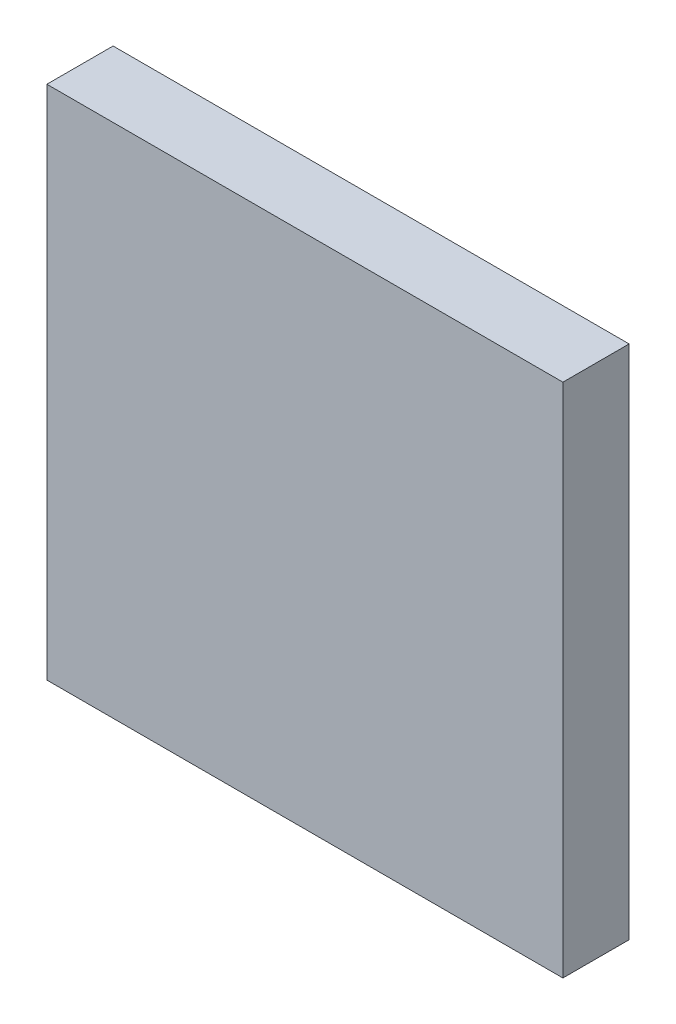
SolidWorks part; units mm, degrees
ref_plane "正面" through (0, 0, 0) normal (0, 0, 1) x (1, 0, 0)
ref_plane "平面" through (0, 0, 0) normal (0, 1, 0) x (1, 0, 0)
ref_plane "右側面" through (0, 0, 0) normal (1, 0, 0) x (0, 0, -1)
sketch "ｽｹｯﾁ1" plane through (0, 0, 0) normal (0, 0, 1) x (1, 0, 0)
  line L0 (-50, 0) -> (50, 0) construction
  line L1 (-50, 50) -> (50, 50)
  line L2 (-50, 50) -> (-50, -50)
  line L3 (-50, -50) -> (50, -50)
  line L4 (50, 50) -> (50, -50)
  line L5 (0, -50) -> (0, 50) construction
  point P8 (0, 0)
  dimension "D1" = 100
  dimension "D2" = 100
  dimension "D3" = 0
  dimension "D4" = 0
extrude "ﾎﾞｽ - 押し出し1" add sketch "ｽｹｯﾁ1" along normal blind 1.6
sketch "ｽｹｯﾁ4" plane through (0, 0, 0) normal (0, 0, -1) x (-1, 0, 0)
  line L0 (-50, -50) -> (-50, 50) construction
  line L1 (11.11, -41.35) -> (28.89, -41.35)
  line L2 (11.11, -41.35) -> (11.11, -43.85)
  line L3 (11.11, -43.85) -> (28.89, -43.85)
  line L4 (28.89, -41.35) -> (28.89, -43.85)
  line L5 (50, -50) -> (-50, -50) construction
  line L6 (50, 50) -> (50, -50) construction
  line L8 (-43.85, -11.11) -> (-41.35, -11.11)
  line L9 (-43.85, -11.11) -> (-43.85, -28.89)
  line L10 (-43.85, -28.89) -> (-41.35, -28.89)
  line L11 (-41.35, -11.11) -> (-41.35, -28.89)
  line L12 (-28.89, 43.85) -> (-11.11, 43.85)
  line L13 (-28.89, 43.85) -> (-28.89, 41.35)
  line L14 (-28.89, 41.35) -> (-11.11, 41.35)
  line L15 (-11.11, 43.85) -> (-11.11, 41.35)
  line L16 (-50, 50) -> (50, 50) construction
  line L18 (41.35, 28.89) -> (43.85, 28.89)
  line L19 (41.35, 28.89) -> (41.35, 11.11)
  line L20 (41.35, 11.11) -> (43.85, 11.11)
  line L21 (43.85, 28.89) -> (43.85, 11.11)
  point P4 (28.89, -42.6)
  point P7 (20, -43.85)
  point P14 (-43.85, -20)
  point P15 (-42.6, -28.89)
  point P22 (-28.89, 42.6)
  point P25 (43.85, 20)
  point P26 (-20, 43.85)
  point P31 (42.6, 28.89)
  dimension "D1" = 7.4
  dimension "D2" = 30
  dimension "D3" = 2.5
  dimension "D4" = 17.78
  dimension "D5" = 2.5
  dimension "D6" = 17.78
  dimension "D7" = 30
  dimension "D8" = 7.4
  dimension "D9" = 2.5
  dimension "D10" = 7.4
  dimension "D11" = 30
  dimension "D12" = 17.78
  dimension "D13" = 17.78
  dimension "D14" = 2.5
  dimension "D15" = 30
  dimension "D16" = 7.4
extrude "ﾎﾞｽ - 押し出し2" add sketch "ｽｹｯﾁ4" along normal blind 2.5
sketch "ｽｹｯﾁ5" plane through (0, 0, -2.5) normal (0, 0, -1) x (-1, 0, 0)
  line L1 (-20.32, 42.92) -> (-19.68, 42.92)
  line L2 (-20.32, 42.92) -> (-20.32, 42.28)
  line L3 (-20.32, 42.28) -> (-19.68, 42.28)
  line L4 (-19.68, 42.92) -> (-19.68, 42.28)
  line L5 (43.85, 28.89) -> (41.35, 28.89) construction
  line L6 (-11.11, 43.85) -> (-28.89, 43.85) construction
  line L7 (-28.89, 43.85) -> (-28.89, 41.35) construction
  line L8 (-43.85, -28.89) -> (-41.35, -28.89) construction
  line L9 (-17.78, 42.92) -> (-17.14, 42.92)
  line L10 (-17.78, 42.92) -> (-17.78, 42.28)
  line L11 (-17.78, 42.28) -> (-17.14, 42.28)
  line L12 (-17.14, 42.92) -> (-17.14, 42.28)
  line L13 (-15.24, 42.92) -> (-14.6, 42.92)
  line L14 (-15.24, 42.92) -> (-15.24, 42.28)
  line L15 (-15.24, 42.28) -> (-14.6, 42.28)
  line L16 (-14.6, 42.92) -> (-14.6, 42.28)
  line L17 (-12.7, 42.92) -> (-12.06, 42.92)
  line L18 (-12.7, 42.92) -> (-12.7, 42.28)
  line L19 (-12.7, 42.28) -> (-12.06, 42.28)
  line L20 (-12.06, 42.92) -> (-12.06, 42.28)
  line L21 (-22.86, 42.92) -> (-22.22, 42.92)
  line L22 (-22.86, 42.92) -> (-22.86, 42.28)
  line L23 (-22.86, 42.28) -> (-22.22, 42.28)
  line L24 (-22.22, 42.92) -> (-22.22, 42.28)
  line L25 (-25.4, 42.92) -> (-24.76, 42.92)
  line L26 (-25.4, 42.92) -> (-25.4, 42.28)
  line L27 (-25.4, 42.28) -> (-24.76, 42.28)
  line L28 (-24.76, 42.92) -> (-24.76, 42.28)
  line L29 (-27.94, 42.92) -> (-27.3, 42.92)
  line L30 (-27.94, 42.92) -> (-27.94, 42.28)
  line L31 (-27.94, 42.28) -> (-27.3, 42.28)
  line L32 (-27.3, 42.92) -> (-27.3, 42.28)
  line L33 (-42.92, -19.68) -> (-42.28, -19.68)
  line L34 (-42.92, -19.68) -> (-42.92, -20.32)
  line L35 (-42.92, -20.32) -> (-42.28, -20.32)
  line L36 (-42.28, -19.68) -> (-42.28, -20.32)
  line L37 (-43.85, -11.11) -> (-43.85, -28.89) construction
  line L38 (43.85, 11.11) -> (43.85, 28.89) construction
  line L39 (-42.92, -22.22) -> (-42.28, -22.22)
  line L40 (-42.92, -22.22) -> (-42.92, -22.86)
  line L41 (-42.92, -22.86) -> (-42.28, -22.86)
  line L42 (-42.28, -22.22) -> (-42.28, -22.86)
  line L44 (42.28, 19.68) -> (42.92, 19.68)
  line L45 (-42.92, -24.76) -> (-42.28, -24.76)
  line L46 (-42.92, -24.76) -> (-42.92, -25.4)
  line L47 (-42.92, -25.4) -> (-42.28, -25.4)
  line L48 (-42.28, -24.76) -> (-42.28, -25.4)
  line L49 (-42.92, -27.3) -> (-42.28, -27.3)
  line L50 (-42.92, -27.3) -> (-42.92, -27.94)
  line L51 (-42.92, -27.94) -> (-42.28, -27.94)
  line L52 (-42.28, -27.3) -> (-42.28, -27.94)
  line L53 (-42.92, -17.14) -> (-42.28, -17.14)
  line L54 (-42.92, -17.14) -> (-42.92, -17.78)
  line L55 (-42.92, -17.78) -> (-42.28, -17.78)
  line L56 (-42.28, -17.14) -> (-42.28, -17.78)
  line L57 (-42.92, -14.6) -> (-42.28, -14.6)
  line L58 (-42.92, -14.6) -> (-42.92, -15.24)
  line L59 (-42.92, -15.24) -> (-42.28, -15.24)
  line L60 (-42.28, -14.6) -> (-42.28, -15.24)
  line L61 (-42.92, -12.06) -> (-42.28, -12.06)
  line L62 (-42.92, -12.06) -> (-42.92, -12.7)
  line L63 (-42.92, -12.7) -> (-42.28, -12.7)
  line L64 (-42.28, -12.06) -> (-42.28, -12.7)
  line L69 (42.28, 19.68) -> (42.28, 20.32)
  line L70 (11.11, -43.85) -> (28.89, -43.85) construction
  line L71 (42.28, 17.78) -> (42.92, 17.78)
  line L72 (42.28, 20.32) -> (42.92, 20.32)
  line L73 (42.92, 19.68) -> (42.92, 20.32)
  line L75 (42.28, 17.78) -> (42.28, 17.14)
  line L76 (42.28, 17.14) -> (42.92, 17.14)
  line L77 (42.92, 17.78) -> (42.92, 17.14)
  line L78 (42.28, 15.24) -> (42.92, 15.24)
  line L79 (42.28, 15.24) -> (42.28, 14.6)
  line L80 (42.28, 14.6) -> (42.92, 14.6)
  line L81 (42.92, 15.24) -> (42.92, 14.6)
  line L82 (42.28, 12.7) -> (42.92, 12.7)
  line L83 (42.28, 12.7) -> (42.28, 12.06)
  line L84 (42.28, 12.06) -> (42.92, 12.06)
  line L85 (42.92, 12.7) -> (42.92, 12.06)
  line L86 (42.28, 22.86) -> (42.92, 22.86)
  line L87 (42.28, 22.86) -> (42.28, 22.22)
  line L88 (42.28, 22.22) -> (42.92, 22.22)
  line L89 (42.92, 22.86) -> (42.92, 22.22)
  line L90 (42.28, 25.4) -> (42.92, 25.4)
  line L91 (42.28, 25.4) -> (42.28, 24.76)
  line L92 (42.28, 24.76) -> (42.92, 24.76)
  line L93 (42.92, 25.4) -> (42.92, 24.76)
  line L94 (42.28, 27.94) -> (42.92, 27.94)
  line L95 (42.28, 27.94) -> (42.28, 27.3)
  line L96 (42.28, 27.3) -> (42.92, 27.3)
  line L97 (42.92, 27.94) -> (42.92, 27.3)
  line L98 (19.68, -42.28) -> (20.32, -42.28)
  line L99 (19.68, -42.28) -> (19.68, -42.92)
  line L100 (19.68, -42.92) -> (20.32, -42.92)
  line L101 (20.32, -42.28) -> (20.32, -42.92)
  line L102 (11.11, -41.35) -> (11.11, -43.85) construction
  line L104 (17.14, -42.28) -> (17.78, -42.28)
  line L105 (17.14, -42.28) -> (17.14, -42.92)
  line L106 (17.14, -42.92) -> (17.78, -42.92)
  line L107 (17.78, -42.28) -> (17.78, -42.92)
  line L108 (14.6, -42.28) -> (15.24, -42.28)
  line L109 (14.6, -42.28) -> (14.6, -42.92)
  line L110 (14.6, -42.92) -> (15.24, -42.92)
  line L111 (15.24, -42.28) -> (15.24, -42.92)
  line L112 (12.06, -42.28) -> (12.7, -42.28)
  line L113 (12.06, -42.28) -> (12.06, -42.92)
  line L114 (12.06, -42.92) -> (12.7, -42.92)
  line L115 (12.7, -42.28) -> (12.7, -42.92)
  line L116 (22.22, -42.28) -> (22.86, -42.28)
  line L117 (22.22, -42.28) -> (22.22, -42.92)
  line L118 (22.22, -42.92) -> (22.86, -42.92)
  line L119 (22.86, -42.28) -> (22.86, -42.92)
  line L120 (24.76, -42.28) -> (25.4, -42.28)
  line L121 (24.76, -42.28) -> (24.76, -42.92)
  line L122 (24.76, -42.92) -> (25.4, -42.92)
  line L123 (25.4, -42.28) -> (25.4, -42.92)
  line L124 (27.3, -42.28) -> (27.94, -42.28)
  line L125 (27.3, -42.28) -> (27.3, -42.92)
  line L126 (27.3, -42.92) -> (27.94, -42.92)
  line L127 (27.94, -42.28) -> (27.94, -42.92)
  point P4 (-20, 42.92)
  point P7 (-20, 43.85)
  point P8 (-20.32, 42.6)
  point P11 (-28.89, 42.6)
  point P16 (-20, 42.28)
  point P17 (-17.46, 42.28)
  point P22 (-14.92, 42.28)
  point P27 (-12.38, 42.28)
  point P40 (-22.54, 42.28)
  point P41 (-25.08, 42.28)
  point P42 (-27.62, 42.28)
  point P47 (-42.6, -20.32)
  point P50 (-42.6, -28.89)
  point P53 (-42.92, -20)
  point P54 (-43.85, -20)
  point P59 (-42.28, -22.54)
  point P60 (-42.28, -20)
  point P61 (-42.28, -25.08)
  point P70 (-42.28, -27.62)
  point P83 (-42.28, -17.46)
  point P84 (-42.28, -14.92)
  point P85 (-42.28, -12.38)
  point P90 (42.6, 19.68)
  point P93 (42.6, 28.89)
  point P94 (42.92, 20)
  point P97 (43.85, 20)
  point P110 (42.28, 12.38)
  point P111 (42.28, 14.92)
  point P112 (42.28, 17.46)
  point P113 (42.28, 20)
  point P126 (42.28, 22.54)
  point P127 (42.28, 25.08)
  point P128 (42.28, 27.62)
  point P133 (20, -42.92)
  point P136 (20, -43.85)
  point P139 (11.11, -42.6)
  point P140 (19.68, -42.6)
  point P165 (17.46, -42.28)
  point P166 (20, -42.28)
  point P167 (14.92, -42.28)
  point P168 (12.38, -42.28)
  point P169 (22.54, -42.28)
  point P170 (25.08, -42.28)
  point P171 (27.62, -42.28)
  point P173 (12.06, -42.6)
  point P174 (14.6, -42.6)
  point P175 (17.14, -42.6)
  point P176 (22.22, -42.6)
  point P177 (24.76, -42.6)
  point P178 (27.3, -42.6)
  point P179 (-42.6, -27.3)
  point P180 (-42.6, -24.76)
  point P181 (-42.6, -22.22)
  point P182 (-42.6, -19.68)
  point P183 (-42.6, -17.14)
  point P184 (-42.6, -14.6)
  point P185 (-42.6, -12.06)
  point P186 (-27.94, 42.6)
  point P187 (-25.4, 42.6)
  point P188 (-22.86, 42.6)
  point P189 (-17.78, 42.6)
  point P190 (-15.24, 42.6)
  point P191 (-12.7, 42.6)
  point P192 (42.6, 15.24)
  point P193 (42.6, 17.78)
  point P194 (42.6, 20.32)
  point P195 (42.6, 22.86)
  point P196 (42.6, 25.4)
  point P197 (42.6, 27.94)
  point P198 (42.6, 12.7)
  dimension "D1" = 0.64
  dimension "D2" = 0.64
  dimension "D3" = 0.64
  dimension "D4" = 0.64
  dimension "D5" = 2.54
  dimension "D6" = 0.64
  dimension "D7" = 2.54
  dimension "D8" = 0.64
  dimension "D9" = 0.64
  dimension "D10" = 0.64
  dimension "D11" = 2.54
  dimension "D12" = 0.64
  dimension "D13" = 0.64
  dimension "D14" = 0.64
  dimension "D15" = 2.54
  dimension "D16" = 0.64
  dimension "D17" = 0.64
  dimension "D18" = 0.64
  dimension "D19" = 2.54
  dimension "D20" = 2.54
  dimension "D21" = 0.64
  dimension "D22" = 0.64
  dimension "D23" = 0.64
  dimension "D24" = 0.64
  dimension "D25" = 2.54
  dimension "D26" = 0.64
  dimension "D27" = 2.54
  dimension "D28" = 0.64
  dimension "D29" = 2.54
  dimension "D30" = 0.64
  dimension "D31" = 0.64
  dimension "D32" = 0.64
  dimension "D33" = 0.64
  dimension "D34" = 2.54
  dimension "D35" = 2.54
  dimension "D36" = 0.64
  dimension "D37" = 0.64
  dimension "D38" = 0.64
  dimension "D39" = 2.54
  dimension "D40" = 0.64
  dimension "D41" = 0.64
  dimension "D42" = 0.64
  dimension "D43" = 0.64
  dimension "D44" = 0.64
  dimension "D45" = 0.64
  dimension "D46" = 2.54
  dimension "D47" = 2.54
  dimension "D48" = 2.54
  dimension "D49" = 2.54
  dimension "D50" = 0.64
  dimension "D51" = 0.64
  dimension "D52" = 0.64
  dimension "D53" = 0.64
  dimension "D54" = 2.54
  dimension "D55" = 0.64
  dimension "D56" = 0.64
  dimension "D57" = 2.54
  dimension "D58" = 0.64
  dimension "D59" = 0.64
  dimension "D60" = 0.64
  dimension "D61" = 0.64
  dimension "D62" = 0.64
  dimension "D63" = 2.54
  dimension "D64" = 2.54
  dimension "D65" = 2.54
  dimension "D66" = 0.64
  dimension "D67" = 0.64
  dimension "D68" = 0.64
  dimension "D69" = 0.64
  dimension "D70" = 0.64
  dimension "D71" = 0.64
  dimension "D72" = 2.54
  dimension "D73" = 2.54
  dimension "D74" = 2.54
  dimension "D75" = 0.64
  dimension "D76" = 0.64
  dimension "D77" = 0.64
  dimension "D78" = 0.64
  dimension "D79" = 0.64
  dimension "D80" = 0.64
extrude "ﾎﾞｽ - 押し出し3" add sketch "ｽｹｯﾁ5" along normal blind 6.1
sketch "ｽｹｯﾁ6" plane through (0, 0, 1.6) normal (0, 0, 1) x (1, 0, 0)
  line L0 (-50, -50) -> (50, -50) construction
  line L1 (-36.74, -33.26) -> (-33.26, -33.26)
  line L2 (-36.74, -33.26) -> (-36.74, -36.74)
  line L3 (-36.74, -36.74) -> (-33.26, -36.74)
  line L4 (-33.26, -33.26) -> (-33.26, -36.74)
  line L5 (-50, 50) -> (-50, -50) construction
  line L6 (50, 50) -> (-50, 50) construction
  line L7 (-36.74, 36.74) -> (-33.26, 36.74)
  line L8 (-36.74, 36.74) -> (-36.74, 33.26)
  line L9 (-36.74, 33.26) -> (-33.26, 33.26)
  line L10 (-33.26, 36.74) -> (-33.26, 33.26)
  line L11 (50, -50) -> (50, 50) construction
  line L12 (33.26, -33.26) -> (36.74, -33.26)
  line L13 (33.26, -33.26) -> (33.26, -36.74)
  line L14 (33.26, -36.74) -> (36.74, -36.74)
  line L15 (36.74, -33.26) -> (36.74, -36.74)
  line L17 (33.26, 36.74) -> (36.74, 36.74)
  line L18 (33.26, 36.74) -> (33.26, 33.26)
  line L19 (33.26, 33.26) -> (36.74, 33.26)
  line L20 (36.74, 36.74) -> (36.74, 33.26)
  point P4 (-36.74, -35)
  point P7 (-35, -36.74)
  point P14 (-36.74, 35)
  point P17 (-35, 36.74)
  point P22 (35, -36.74)
  point P25 (36.74, -35)
  point P30 (35, 36.74)
  point P31 (36.74, 35)
  dimension "D1" = 3.48
  dimension "D2" = 3.48
  dimension "D3" = 15
  dimension "D4" = 15
  dimension "D5" = 3.48
  dimension "D6" = 3.48
  dimension "D7" = 15
  dimension "D8" = 15
  dimension "D9" = 15
  dimension "D10" = 15
  dimension "D11" = 3.48
  dimension "D12" = 3.48
  dimension "D13" = 15
  dimension "D14" = 15
  dimension "D15" = 3.48
  dimension "D16" = 3.48
extrude "ﾎﾞｽ - 押し出し4" add sketch "ｽｹｯﾁ6" along normal blind 2
sketch "ｽｹｯﾁ7" plane through (0, 0, 1.6) normal (0, 0, 1) x (1, 0, 0)
  line L0 (-50, -50) -> (50, -50) construction
  line L1 (-38.5, 2) -> (-36.5, 2)
  line L2 (-38.5, 2) -> (-38.5, -2)
  line L3 (-38.5, -2) -> (-36.5, -2)
  line L4 (-36.5, 2) -> (-36.5, -2)
  line L5 (-50, 50) -> (-50, -50) construction
  line L6 (50, -50) -> (50, 50) construction
  line L7 (36.5, 2) -> (38.5, 2)
  line L8 (36.5, 2) -> (36.5, -2)
  line L9 (36.5, -2) -> (38.5, -2)
  line L10 (38.5, 2) -> (38.5, -2)
  line L11 (50, 50) -> (-50, 50) construction
  line L12 (-2, 38.5) -> (2, 38.5)
  line L13 (-2, 38.5) -> (-2, 36.5)
  line L14 (-2, 36.5) -> (2, 36.5)
  line L15 (2, 38.5) -> (2, 36.5)
  line L17 (-2, -36.5) -> (2, -36.5)
  line L18 (-2, -36.5) -> (-2, -38.5)
  line L19 (-2, -38.5) -> (2, -38.5)
  line L20 (2, -36.5) -> (2, -38.5)
  line L21 (-1, 2) -> (1, 2)
  line L22 (-1, 2) -> (-1, -2)
  line L23 (-1, -2) -> (1, -2)
  line L24 (1, 2) -> (1, -2)
  point P4 (-38.5, 0)
  point P7 (-37.5, -2)
  point P14 (37.5, 2)
  point P17 (38.5, 0)
  point P22 (-2, 37.5)
  point P25 (0, 38.5)
  point P30 (-2, -37.5)
  point P31 (0, -38.5)
  point P36 (1, 0)
  point P37 (36.5, 0)
  point P38 (0, 36.5)
  point P39 (0, 2)
  dimension "D1" = 4
  dimension "D2" = 2
  dimension "D3" = 50
  dimension "D4" = 12.5
  dimension "D5" = 4
  dimension "D6" = 2
  dimension "D7" = 12.5
  dimension "D8" = 50
  dimension "D9" = 4
  dimension "D10" = 2
  dimension "D11" = 12.5
  dimension "D12" = 50
  dimension "D13" = 4
  dimension "D14" = 2
  dimension "D15" = 12.5
  dimension "D16" = 50
  dimension "D17" = 4
  dimension "D18" = 2
extrude "ﾎﾞｽ - 押し出し5" add sketch "ｽｹｯﾁ7" along normal blind 1.1
sketch "ｽｹｯﾁ8" plane through (0, 0, 1.6) normal (0, 0, 1) x (1, 0, 0)
  line L0 (-50, -50) -> (50, -50) construction
  line L1 (-7.6, -13.3) -> (7.6, -13.3)
  line L2 (-7.6, -13.3) -> (-7.6, -20.7)
  line L3 (-7.6, -20.7) -> (7.6, -20.7)
  line L4 (7.6, -13.3) -> (7.6, -20.7)
  point P4 (-7.6, -17)
  point P7 (0, -50)
  point P8 (0, -20.7)
  dimension "D1" = 7.4
  dimension "D2" = 15.2
  dimension "D3" = 33
extrude "ﾎﾞｽ - 押し出し6" add sketch "ｽｹｯﾁ8" along normal blind 2.65
sketch "ｽｹｯﾁ9" plane through (0, 0, 0) normal (0, 0, -1) x (-1, 0, 0)
  line L1 (-4.61, 19.83) -> (3.01, 19.83)
  line L2 (-4.61, 19.83) -> (-4.61, 17.33)
  line L3 (-4.61, 17.33) -> (3.01, 17.33)
  line L4 (3.01, 19.83) -> (3.01, 17.33)
  line L5 (50, 50) -> (50, -50) construction
  line L6 (50, -50) -> (-50, -50) construction
  point P4 (-0.8, 19.83)
  point P7 (3.01, 18.58)
  dimension "D1" = 7.62
  dimension "D2" = 2.5
  dimension "D3" = 50.8
  dimension "D4" = 68.58
extrude "ﾎﾞｽ - 押し出し7" add sketch "ｽｹｯﾁ9" along normal blind 2.5
sketch "ｽｹｯﾁ11" plane through (0, 0, -2.5) normal (0, 0, -1) x (-1, 0, 0)
  line L0 (3.01, 19.83) -> (-4.61, 19.83) construction
  line L1 (-1.12, 18.9) -> (-0.48, 18.9)
  line L2 (-1.12, 18.9) -> (-1.12, 18.26)
  line L3 (-1.12, 18.26) -> (-0.48, 18.26)
  line L4 (-0.48, 18.9) -> (-0.48, 18.26)
  line L5 (-4.61, 19.83) -> (-4.61, 17.33) construction
  line L7 (-3.66, 18.9) -> (-3.02, 18.9)
  line L8 (-3.66, 18.9) -> (-3.66, 18.26)
  line L9 (-3.66, 18.26) -> (-3.02, 18.26)
  line L10 (-3.02, 18.9) -> (-3.02, 18.26)
  line L11 (1.42, 18.9) -> (2.06, 18.9)
  line L12 (1.42, 18.9) -> (1.42, 18.26)
  line L13 (1.42, 18.26) -> (2.06, 18.26)
  line L14 (2.06, 18.9) -> (2.06, 18.26)
  point P4 (-0.8, 18.9)
  point P7 (-0.8, 19.83)
  point P8 (-1.12, 18.58)
  point P11 (-4.61, 18.58)
  point P20 (-3.34, 18.26)
  point P21 (-0.8, 18.26)
  point P22 (1.74, 18.26)
  point P23 (-3.66, 18.58)
  point P25 (1.42, 18.58)
  dimension "D1" = 0.64
  dimension "D2" = 0.64
  dimension "D3" = 0.64
  dimension "D4" = 0.64
  dimension "D5" = 0.64
  dimension "D6" = 2.54
  dimension "D7" = 2.54
extrude "ﾎﾞｽ - 押し出し8" add sketch "ｽｹｯﾁ11" along normal blind 6.1
sketch "ｽｹｯﾁ16" plane through (0, 0, 0) normal (0, 0, -1) x (-1, 0, 0)
  line L0 (50, -50) -> (-50, -50) construction
  line L1 (-5.08, -29.75) -> (5.08, -29.75)
  line L2 (-5.08, -29.75) -> (-5.08, -32.25)
  line L3 (-5.08, -32.25) -> (5.08, -32.25)
  line L4 (5.08, -29.75) -> (5.08, -32.25)
  line L5 (0, 0) -> (0, -50) construction
  point P4 (-5.08, -31)
  point P10 (0, -32.25)
  dimension "D1" = 2.5
  dimension "D2" = 10.16
  dimension "D3" = 19
extrude "ﾎﾞｽ - 押し出し12" add sketch "ｽｹｯﾁ16" along normal blind 2.5
sketch "ｽｹｯﾁ17" plane through (0, 0, -2.5) normal (0, 0, -1) x (-1, 0, 0)
  line L0 (-5.08, -31) -> (5.08, -31) construction
  line L1 (-4.13, -30.68) -> (-3.49, -30.68)
  line L2 (-4.13, -30.68) -> (-4.13, -31.32)
  line L3 (-4.13, -31.32) -> (-3.49, -31.32)
  line L4 (-3.49, -30.68) -> (-3.49, -31.32)
  line L5 (-1.59, -30.68) -> (-0.95, -30.68)
  line L6 (-1.59, -30.68) -> (-1.59, -31.32)
  line L7 (-1.59, -31.32) -> (-0.95, -31.32)
  line L8 (-0.95, -30.68) -> (-0.95, -31.32)
  line L9 (0.95, -30.68) -> (1.59, -30.68)
  line L10 (0.95, -30.68) -> (0.95, -31.32)
  line L11 (0.95, -31.32) -> (1.59, -31.32)
  line L12 (1.59, -30.68) -> (1.59, -31.32)
  line L13 (3.49, -30.68) -> (4.13, -30.68)
  line L14 (3.49, -30.68) -> (3.49, -31.32)
  line L15 (3.49, -31.32) -> (4.13, -31.32)
  line L16 (4.13, -30.68) -> (4.13, -31.32)
  line L17 (-5.08, -29.75) -> (-5.08, -32.25) construction
  line L18 (5.08, -32.25) -> (5.08, -29.75) construction
  point P22 (-4.13, -31)
  point P23 (-1.59, -31)
  point P24 (0.95, -31)
  point P25 (3.49, -31)
  point P26 (-3.81, -31.32)
  point P27 (-1.27, -31.32)
  point P28 (3.81, -31.32)
  point P29 (1.27, -31.32)
  dimension "D1" = 0.64
  dimension "D2" = 0.64
  dimension "D3" = 0.64
  dimension "D4" = 0.64
  dimension "D5" = 0.64
  dimension "D6" = 2.54
  dimension "D7" = 2.54
  dimension "D8" = 2.54
  dimension "D9" = 1.27
extrude "ﾎﾞｽ - 押し出し13" add sketch "ｽｹｯﾁ17" along normal blind 6.1
sketch "ｽｹｯﾁ13" plane through (0, 0, 0) normal (0, 0, -1) x (-1, 0, 0)
  line L0 (-50, -50) -> (-50, 50) construction
  line L7 (-50, 50) -> (50, 50) construction
  line L8 (50, -50) -> (-50, -50) construction
  line L15 (50, 50) -> (50, -50) construction
  line L23 (32, -30) -> (31, -28.2679)
  line L24 (31, -28.2679) -> (29, -28.2679)
  line L25 (29, -28.2679) -> (28, -30)
  line L26 (28, -30) -> (29, -31.7321)
  line L27 (29, -31.7321) -> (31, -31.7321)
  line L28 (31, -31.7321) -> (32, -30)
  line L29 (-28, -30) -> (-29, -28.2679)
  line L30 (-29, -28.2679) -> (-31, -28.2679)
  line L31 (-31, -28.2679) -> (-32, -30)
  line L32 (-32, -30) -> (-31, -31.7321)
  line L33 (-31, -31.7321) -> (-29, -31.7321)
  line L34 (-29, -31.7321) -> (-28, -30)
  line L35 (32, 30) -> (31, 31.7321)
  line L36 (31, 31.7321) -> (29, 31.7321)
  line L37 (29, 31.7321) -> (28, 30)
  line L38 (28, 30) -> (29, 28.2679)
  line L39 (29, 28.2679) -> (31, 28.2679)
  line L40 (31, 28.2679) -> (32, 30)
  line L41 (-28, 30) -> (-29, 31.7321)
  line L42 (-29, 31.7321) -> (-31, 31.7321)
  line L43 (-31, 31.7321) -> (-32, 30)
  line L44 (-32, 30) -> (-31, 28.2679)
  line L45 (-31, 28.2679) -> (-29, 28.2679)
  line L46 (-29, 28.2679) -> (-28, 30)
  circle A0 centre (-30, 30) radius 2 construction
  circle A1 centre (-30, -30) radius 2 construction
  circle A2 centre (30, 30) radius 2 construction
  circle A3 centre (30, -30) radius 2 construction
  dimension "D1" = 20
  dimension "D2" = 20
  dimension "D3" = 20
  dimension "D4" = 20
  dimension "D5" = 20
  dimension "D6" = 20
  dimension "D7" = 20
  dimension "D8" = 20
extrude "ﾎﾞｽ - 押し出し9" add sketch "ｽｹｯﾁ13" along normal blind 6
sketch "ｽｹｯﾁ14" plane through (0, 0, -6) normal (0, 0, -1) x (-1, 0, 0)
  line L2 (0, -39) -> (0, -41)
  line L3 (0, -41) -> (39, -41)
  line L4 (39, -41) -> (39, 0)
  line L5 (39, 0) -> (41, 0)
  line L6 (41, 0) -> (41, 39)
  line L7 (41, 39) -> (0, 39)
  line L8 (0, 39) -> (0, 41)
  line L9 (0, 41) -> (-39, 41)
  line L11 (-39, 41) -> (-39, 0)
  line L12 (-39, 0) -> (-41, 0)
  line L13 (-41, 0) -> (-41, -39)
  line L14 (-41, -39) -> (0, -39)
  line L15 (-5.08, -32.25) -> (5.08, -32.25) construction
  line L21 (-29, 31.7321) -> (-31, 31.7321) construction
  line L22 (-4.61, 19.83) -> (3.01, 19.83)
  line L23 (-4.61, 19.83) -> (-4.61, 17.33)
  line L24 (-4.61, 17.33) -> (3.01, 17.33)
  line L25 (3.01, 19.83) -> (3.01, 17.33)
  line L26 (31, 31.7321) -> (29, 31.7321) construction
  line L27 (31, -28.2679) -> (29, -28.2679) construction
  line L28 (-29, -28.2679) -> (-31, -28.2679) construction
  line L29 (-5.08, -29.75) -> (5.08, -29.75)
  line L30 (-5.08, -29.75) -> (-5.08, -32.25)
  line L31 (-5.08, -32.25) -> (5.08, -32.25)
  line L32 (5.08, -29.75) -> (5.08, -32.25)
  line L33 (-5.08, -32.25) -> (5.08, -32.25) construction
  circle A0 centre (-30, 30) radius 1
  circle A1 centre (30, 30) radius 1
  circle A2 centre (30, -30) radius 1
  circle A3 centre (-30, -30) radius 1
  point P28 (-30, 31.7321)
  point P37 (30, 31.7321)
  point P41 (30, -28.2679)
  point P47 (-30, -28.2679)
  dimension "D1" = 39
  dimension "D2" = 41
  dimension "D3" = 41
  dimension "D4" = 39
  dimension "D5" = 41
  dimension "D6" = 39
  dimension "D7" = 41
  dimension "D8" = 39
  dimension "D9" = 2.5
  dimension "D10" = 7.62
extrude "ﾎﾞｽ - 押し出し10" add sketch "ｽｹｯﾁ14" along normal blind 2 separate body
sketch "ｽｹｯﾁ15" plane through (0, 0, -2.5) normal (0, 0, -1) x (-1, 0, 0)
  line L1 (-60, 60) -> (60, 60)
  line L2 (-60, 60) -> (-60, -60)
  line L3 (-60, -60) -> (60, -60)
  line L4 (60, 60) -> (60, -60)
  point P4 (0, 60)
  point P6 (-60, 0)
  dimension "D1" = 120
  dimension "D2" = 120
extrude "ﾎﾞｽ - 押し出し11" add sketch "ｽｹｯﾁ15" against normal blind 15.4 separate body
